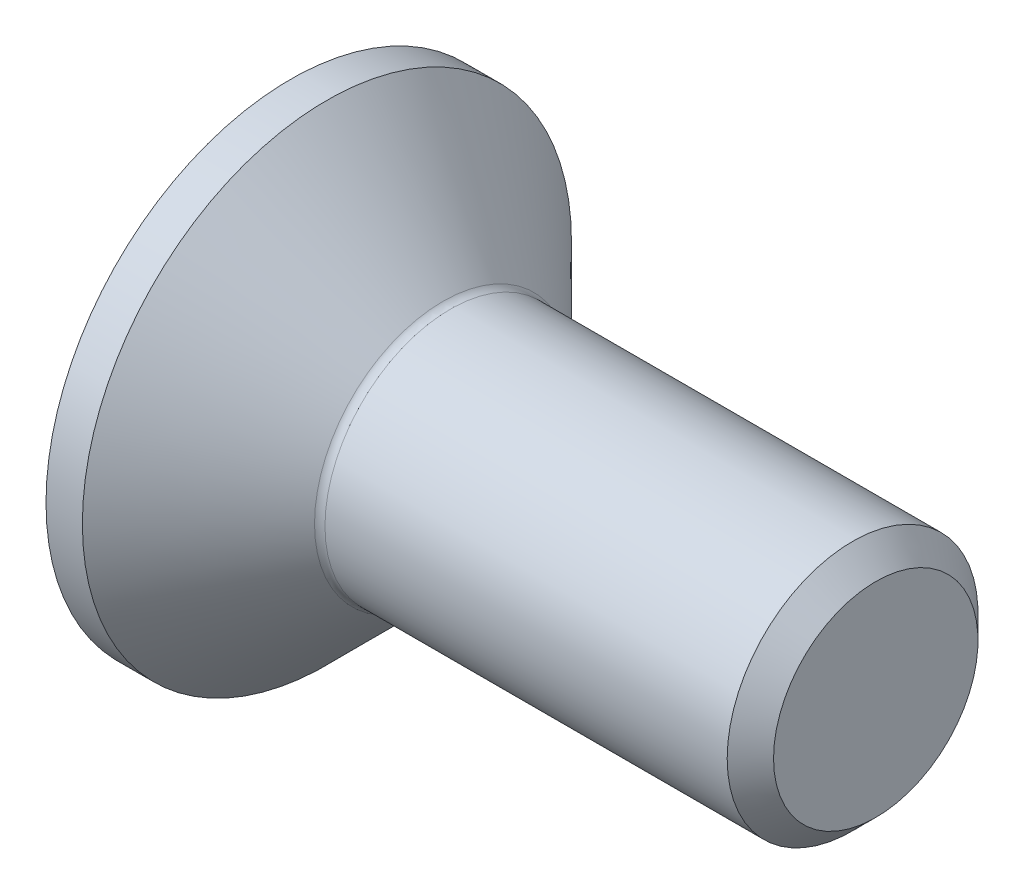
SolidWorks part; units mm, degrees
ref_plane "Plane1" through (0, 0, 0) normal (0, 0, 1) x (1, 0, 0)
ref_plane "Plane2" through (0, 0, 0) normal (0, 1, 0) x (1, 0, 0)
ref_plane "Plane3" through (0, 0, 0) normal (1, 0, 0) x (0, 0, -1)
sketch "BodySke" plane through (0, 0, 0) normal (0, 0, 1) x (1, 0, 0)
  line L0 (0, 0) -> (0, 5.85)
  line L1 (0.87, 5.85) -> (3.72, 3)
  line L2 (0, 5.85) -> (0.87, 5.85)
  line L3 (3.72, 3) -> (13.4455, 3)
  line L4 (14, 2.4455) -> (14, 0)
  line L5 (14, 0) -> (0, 0)
  line L6 (0, 0) -> (127, 0) construction
  line L7 (0.87, -5.85) -> (3.72, -3) construction
  line L8 (14, 2.4455) -> (13.4455, 3)
  line L9 (0, -5.85) -> (0.87, -5.85) construction
  line L10 (14, -2.4455) -> (13.4455, -3) construction
  line L11 (4.72, 9.35) -> (4.72, -12.875) construction
  line L12 (2, 19.05) -> (2, -3.175) construction
  dimension "D1" = 0.87
  dimension "Diameter" = 6
  dimension "Head_ht" = 3.72
  dimension "Length" = 14
  dimension "Body_ch_ang" = 45
  dimension "Head_dia" = 11.7
  dimension "Minor_dia" = 4.891
  dimension "Head_ang" = 90
  dimension "Advance" = 1
  dimension "Thread_nom" = 12
revolve "BaseBody" add sketch "BodySke" angle 360 about L6
cosmetic thread "ThreadCosmetic" parameters "Thread_length"=16, "Thread_minor"=4.891
fillet "Fillet1" radius 0.25 1 edges at (3.72, 0, 3)
sketch "Sketch2" plane through (0, 0, 0) normal (0, 0, 1) x (1, 0, 0)
  line L0 (0, 2) -> (2.2, 2)
  line L1 (2.2, 2) -> (3.3547, 0)
  line L2 (0, 0) -> (127, 0) construction
  line L3 (3.3547, 0) -> (0, 0)
  line L4 (0, 0) -> (0, 2)
  line L5 (0, -2) -> (2.2, -2) construction
  line L6 (0, 0) -> (47.625, 0) construction
  line L8 (0, 5.85) -> (0, -5.85) construction
  dimension "D2" = 60
  dimension "PreBroach_depth" = 2.2
  dimension "PreBroach_dia" = 4
revolve "PreBroach" cut sketch "Sketch2" angle 360 about L6
sketch "Sketch3" plane through (0, 0, 0) normal (-1, 0, 0) x (0, 0, 1)
  line L0 (-2, -1.1547) -> (-2, 1.1547)
  line L1 (-2, 1.1547) -> (0, 2.3094)
  line L2 (0, 2.3094) -> (2, 1.1547)
  line L3 (2, 1.1547) -> (2, -1.1547)
  line L4 (2, -1.1547) -> (0, -2.3094)
  line L5 (0, -2.3094) -> (-2, -1.1547)
  dimension "D1" = 2
  dimension "D2" = 2
  dimension "D3" = 4
  dimension "Hex_size" = 4
extrude "Hex" cut sketch "Sketch3" against normal blind 2.2
